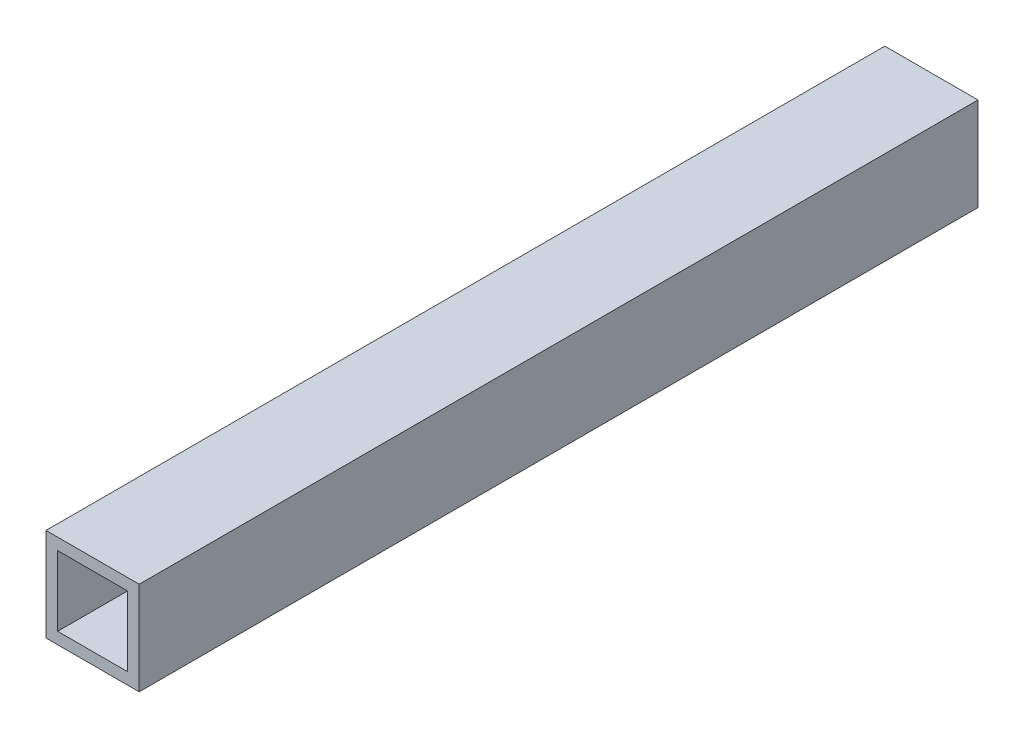
SolidWorks part; units mm, degrees
material "6061 Alloy"
ref_plane "Front Plane" through (0, 0, 0) normal (0, 0, 1) x (1, 0, 0)
ref_plane "Top Plane" through (0, 0, 0) normal (0, 1, 0) x (1, 0, 0)
ref_plane "Right Plane" through (0, 0, 0) normal (1, 0, 0) x (0, 0, -1)
sketch "Sketch1" plane through (0, 0, 0) normal (0, 0, 1) x (1, 0, 0)
  line L0 (12.7, 0) -> (9.525, 0) construction
  line L1 (-12.7, 0) -> (12.7, 0) construction
  line L2 (0, 12.7) -> (0, -12.7)
  point P7 (0, 0)
sketch "Sketch2" plane through (0, 0, 0) normal (1, 0, 0) x (0, 0, -1)
  line L0 (114.3, 0) -> (-114.3, 0)
  point P4 (0, 0)
  dimension "Length" = 228.6
sketch "Sketch3" plane through (0, 0, 0) normal (0, 0, 1) x (1, 0, 0)
  line L0 (-12.7, 0) -> (12.7, 0) construction
  line L5 (12.7, -12.7) -> (-12.7, -12.7)
  line L6 (12.7, -12.7) -> (12.7, 12.7)
  line L11 (12.7, 12.7) -> (-12.7, 12.7)
  line L12 (-12.7, -12.7) -> (-12.7, 12.7)
  line L14 (12.7, -12.7) -> (-12.7, 12.7) construction
  line L15 (12.7, 12.7) -> (-12.7, -12.7) construction
  line L16 (9.525, -9.525) -> (-9.525, -9.525)
  line L17 (9.525, -9.525) -> (9.525, 9.525)
  line L18 (9.525, 9.525) -> (-9.525, 9.525)
  line L19 (-9.525, -9.525) -> (-9.525, 9.525)
  line L20 (9.525, -9.525) -> (-9.525, 9.525) construction
  line L21 (9.525, 9.525) -> (-9.525, -9.525) construction
  point P0 (0, 0)
  point P5 (0, 0)
  point P13 (9.525, -12.7)
  dimension "D1" = 3.175
  dimension "D3" = 25.4
  dimension "D4" = 25.4
extrude "Boss-Extrude1" add sketch "Sketch3" along normal up to vertex (114.3 mm away) and the other way up to vertex (114.3 mm away) up to point (0, 0, 114.3) other way up to point (0, 0, -114.3)
sketch "Sketch5" plane through (0, 0, 0) normal (1, 0, 0) x (0, 0, -1)
  line L0 (-114.3, 0) -> (114.3, 0) construction
  line L3 (-114.3, -12.7) -> (-114.3, 12.7) construction
  line L4 (114.3, -12.7) -> (114.3, 12.7) construction
  point P6 (-85.725, 0)
  point P7 (-76.2, 0)
  point P8 (76.2, 0)
  point P10 (85.725, 0)
  dimension "D1" = 28.575
  dimension "D2" = 38.1
  dimension "D3" = 28.575
  dimension "D4" = 38.1
equation "\"D1@Sketch3\"=\"Wall thickness@Sketch1\""
equation "\"D1@Sketch5\"=\"Width@Sketch1\"*1.125"
equation "\"D2@Sketch5\"=\"Width@Sketch1\"*1.5"
equation "\"D3@Sketch5\"=\"D1@Sketch5\""
equation "\"D4@Sketch5\"=\"D2@Sketch5\""
equation "\"D2@Sketch3\"=\"Wall Thickness@Sketch1\""
